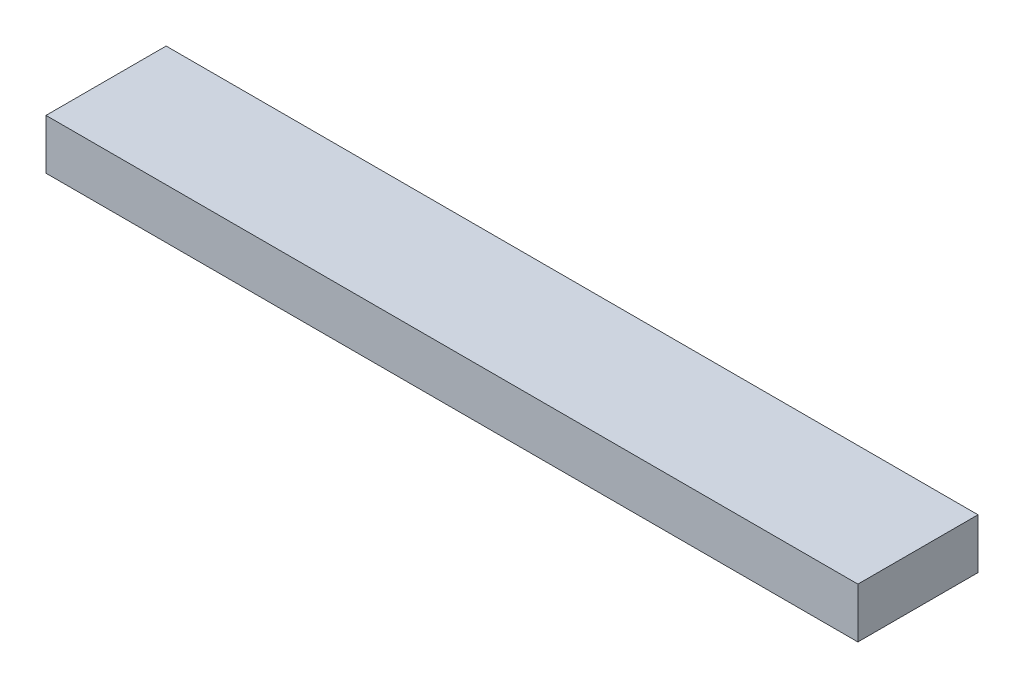
SolidWorks part; units mm, degrees
ref_plane "Front Plane" through (0, 0, 0) normal (0, 0, 1) x (1, 0, 0)
ref_plane "Top Plane" through (0, 0, 0) normal (0, 1, 0) x (1, 0, 0)
ref_plane "Right Plane" through (0, 0, 0) normal (1, 0, 0) x (0, 0, -1)
sketch "Sketch1" plane through (0, 0, 0) normal (0, 1, 0) x (1, 0, 0)
  line L1 (-81, -11.9847) -> (81, -11.9847)
  line L2 (-81, -11.9847) -> (-81, 11.9847)
  line L3 (-81, 11.9847) -> (81, 11.9847)
  line L4 (81, -11.9847) -> (81, 11.9847)
  line L5 (-81, -11.9847) -> (81, 11.9847) construction
  line L6 (-81, 11.9847) -> (81, -11.9847) construction
  point P0 (0, 0)
  dimension "D1" = 162
extrude "Boss-Extrude1" add sketch "Sketch1" along normal blind 10
